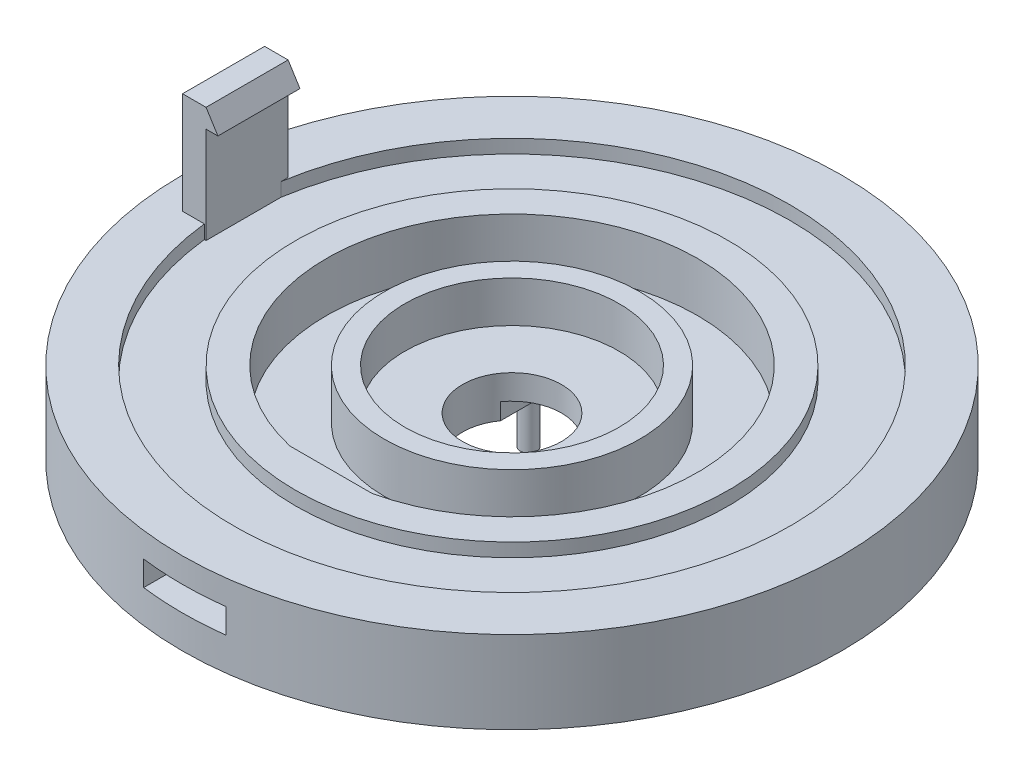
SolidWorks part; units mm, degrees
ref_plane "Front Plane" through (0, 0, 0) normal (0, 0, 1) x (1, 0, 0)
ref_plane "Top Plane" through (0, 0, 0) normal (0, 1, 0) x (1, 0, 0)
ref_plane "Right Plane" through (0, 0, 0) normal (1, 0, 0) x (0, 0, -1)
sketch "Sketch28" plane through (0, 0, 0) normal (0, 1, 0) x (1, 0, 0)
  line L1 (-38.0554, -35.7587) -> (41.9446, -35.7587)
  line L2 (-38.0554, -35.7587) -> (-38.0554, 44.2413)
  line L3 (-38.0554, 44.2413) -> (41.9446, 44.2413)
  line L4 (41.9446, -35.7587) -> (41.9446, 44.2413)
  dimension "D1" = 80
extrude "Boss-Extrude1" add sketch "Sketch28" along normal blind 10
hole_wizard "CBORE for M10 Cheese Head Screw1" positions "Sketch30" profile "Sketch29" counterbore size "M10" standard "AS" end condition through all
sketch "Sketch30" plane through (0, 10, 0) normal (0, 1, 0) x (1, 0, 0)
  point P0 (1.9446, 4.2413)
sketch "Sketch29" plane through (1.9446, 10, -4.2413) normal (1, 0, 0) x (0, 0, 1)
  line L0 (0, 0) -> (0, 10)
  line L1 (0, 10) -> (6, 10)
  line L3 (6, 10) -> (6, 5)
  line L4 (6, 5) -> (13, 5)
  line L5 (13, 5) -> (13, 0)
  line L7 (13, 0) -> (0, 0)
  line L11 (0, -6.35) -> (0, 107.95) construction
  dimension "Thru Hole Dia." = 12
  dimension "Thru Hole Depth" = 10
  dimension "C'Bore Dia." = 26
  dimension "C'Bore Depth" = 5
sketch "Sketch36" plane through (0, 0, 0) normal (0, -1, 0) x (1, 0, 0)
  circle A0 centre (12.4446, -16.7413) radius 1
  circle A1 centre (12.4446, -4.2413) radius 1
  circle A2 centre (-8.5554, -16.7413) radius 1
  circle A3 centre (-8.5554, -4.2413) radius 1
extrude "Boss-Extrude5" add sketch "Sketch36" along normal blind 10
sketch "Sketch37" plane through (0, 10, 0) normal (0, 1, 0) x (1, 0, 0)
  line L0 (1.9446, 44.2413) -> (1.9446, -35.7587) construction
  line L1 (41.9446, 44.2413) -> (-38.0554, 44.2413) construction
  line L2 (-38.0554, -35.7587) -> (41.9446, -35.7587) construction
  line L3 (-38.0554, 4.2413) -> (41.9446, 4.2413) construction
  line L4 (-38.0554, 44.2413) -> (-38.0554, -35.7587) construction
  line L5 (41.9446, -35.7587) -> (41.9446, 44.2413) construction
  circle A0 centre (1.9446, 4.2413) radius 22.5
  circle A1 centre (1.9446, 4.2413) radius 15.5
  dimension "D1" = 31
  dimension "D2" = 45
extrude "Cut-Extrude2" cut sketch "Sketch37" against normal blind 6
sketch "Sketch39" plane through (0, 10, 0) normal (0, 1, 0) x (1, 0, 0)
  line L0 (41.9446, 44.2413) -> (-38.0554, 44.2413) construction
  line L1 (10.8724, 24.8942) -> (-5.6612, 24.8942)
  line L2 (10.8724, 24.8942) -> (10.8724, 44.2413)
  line L3 (10.8724, 44.2413) -> (-5.6612, 44.2413)
  line L4 (-5.6612, 24.8942) -> (-5.6612, 44.2413)
  line L5 (1.9446, -35.7587) -> (6.9446, -35.7587)
  line L6 (-38.0554, -35.7587) -> (41.9446, -35.7587) construction
  line L7 (6.9446, -35.7587) -> (-3.0554, -35.7587)
  line L8 (-3.0554, -35.7587) -> (-3.0554, -17.6961)
  line L9 (-3.0554, -17.6961) -> (6.9446, -17.6961)
  line L10 (6.9446, -17.6961) -> (6.9446, -35.7587)
  circle A0 centre (1.9446, 4.2413) radius 22.5 construction
  circle M5 centre (1.9446, 4.2413) radius 22.5
  line M7 (-38.0554, -35.7587) -> (41.9446, -35.7587)
extrude "Cut-Extrude6" cut sketch "Sketch39" against normal blind 6 contours L10 L8 M5 M7
sketch "Sketch40" plane through (-3.0554, 0, 0) normal (1, 0, 0) x (0, 0, -1)
  line L0 (-35.7587, 4) -> (-35.7587, 10) construction
  line L1 (-35.7587, 7) -> (-17.6961, 7)
  line L2 (-35.7587, 7) -> (-35.7587, 10)
  line L3 (-35.7587, 10) -> (-17.6961, 10)
  line L4 (-17.6961, 7) -> (-17.6961, 10)
extrude "Boss-Extrude7" add sketch "Sketch40" along normal blind 13
sketch "Sketch41" plane through (0, 10, 0) normal (0, 1, 0) x (1, 0, 0)
  circle A0 centre (1.9446, 4.2413) radius 33.75
  circle A1 centre (1.9446, 4.2413) radius 26.25
  dimension "D1" = 67.5
extrude "Cut-Extrude7" cut sketch "Sketch41" against normal blind 1.65
sketch "Sketch42" plane through (0, 0, 0) normal (0, -1, 0) x (1, 0, 0)
  line L0 (-8.5334, -17.7413) -> (-2.9334, -17.7413) construction
  line L1 (12.4446, -17.7413) -> (6.8666, -17.7413) construction
  line L2 (6.8666, -7.591) -> (6.8666, -18.6283)
  line L3 (-2.9334, -18.6283) -> (-2.9334, -7.591)
  line L4 (6.8666, -7.591) -> (-2.9334, -7.591)
  line L5 (6.8666, -18.6283) -> (-2.9334, -18.6283)
  circle A0 centre (12.4446, -16.7413) radius 1 construction
extrude "Cut-Extrude8" cut sketch "Sketch42" against normal blind 2
sketch "Sketch43" plane through (0, 10, 0) normal (0, 1, 0) x (1, 0, 0)
  line L1 (41.9446, 44.2413) -> (-38.0554, 44.2413) construction
  line L2 (1.9446, 44.2413) -> (41.9446, 44.2413)
  line L3 (41.9446, 44.2413) -> (41.9446, -35.7587)
  line L5 (1.9446, 44.2413) -> (-38.0554, 44.2413)
  line L6 (-38.0554, 44.2413) -> (-38.0554, -35.7587)
  line L7 (41.9446, 4.2413) -> (-38.0554, 4.2413) construction
  line L8 (1.9446, -35.7587) -> (41.9446, -35.7587)
  line L9 (1.9446, -35.7587) -> (-38.0554, -35.7587)
  arc A1 (1.9446, -35.7587) -> (1.9446, 44.2413) centre (1.9446, 4.2413) ccw
  arc A2 (1.9446, 44.2413) -> (1.9446, -35.7587) centre (1.9446, 4.2413) ccw
  line M5 (-38.0554, -35.7587) -> (41.9446, -35.7587)
  line M6 (41.9446, -35.7587) -> (41.9446, 44.2413)
  line M7 (41.9446, 44.2413) -> (-38.0554, 44.2413)
  line M8 (-38.0554, 44.2413) -> (-38.0554, -35.7587)
extrude "Cut-Extrude11" cut sketch "Sketch43" against normal blind 20 contours A2 M7 M8 | A2 L6 M5 | A1 M5 M6 | A1 L3 M7
sketch "Sketch45" plane through (0, 8.35, 0) normal (0, 1, 0) x (1, 0, 0)
  line L1 (-34.2365, 10.408) -> (-31.3854, 10.408)
  line L2 (-34.2365, 10.408) -> (-34.2365, 0.4527)
  line L3 (-34.2365, 0.4527) -> (-31.3854, 0.4527)
  line L4 (-31.3854, 10.408) -> (-31.3854, 0.4527)
extrude "Boss-Extrude8" add sketch "Sketch45" along normal blind 14
sketch "Sketch46" plane through (0, 0, -0.4527) normal (0, 0, 1) x (1, 0, 0)
  line L0 (-31.3854, 22.35) -> (-31.3854, 20.0572)
  line L1 (-31.3854, 22.35) -> (-31.3854, 8.35) construction
  line L2 (-31.3854, 20.0572) -> (-29.9445, 20.0572)
  line L3 (-29.9445, 20.0572) -> (-31.3854, 22.35)
extrude "Boss-Extrude9" add sketch "Sketch46" against normal up to vertex (9.9553 mm away) up to point (-31.3855, 22.35, -10.408)
